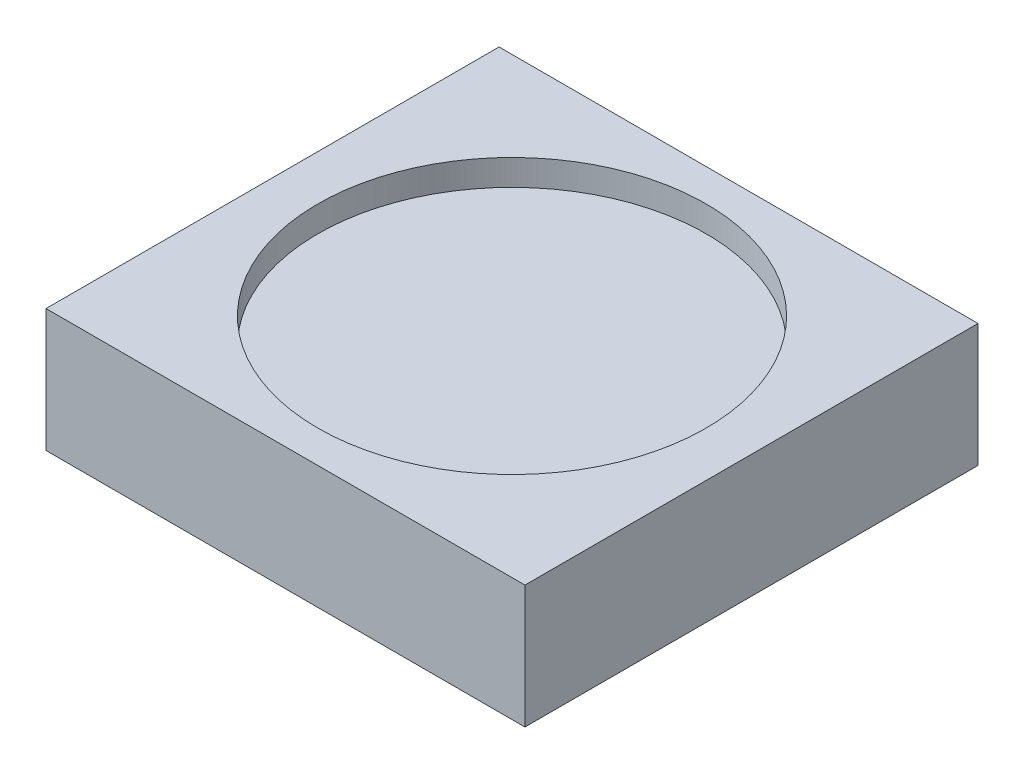
SolidWorks part; units mm, degrees
ref_plane "Front Plane" through (0, 0, 0) normal (0, 0, 1) x (1, 0, 0)
ref_plane "Top Plane" through (0, 0, 0) normal (0, 1, 0) x (1, 0, 0)
ref_plane "Right Plane" through (0, 0, 0) normal (1, 0, 0) x (0, 0, -1)
sketch "Sketch1" plane through (0, 0, 0) normal (0, 1, 0) x (1, 0, 0)
  line L1 (0, 0) -> (3.7, 0)
  line L2 (0, 0) -> (0, 3.5)
  line L3 (0, 3.5) -> (3.7, 3.5)
  line L4 (3.7, 0) -> (3.7, 3.5)
  dimension "D1" = 3.7
  dimension "D2" = 3.5
extrude "Boss-Extrude1" add sketch "Sketch1" along normal blind 0.95
sketch "Sketch2" plane through (0, 0.95, 0) normal (0, 1, 0) x (1, 0, 0)
  line L0 (0, 1.75) -> (3.7, 1.75) construction
  line L1 (0, 3.5) -> (0, 0) construction
  line L2 (3.7, 0) -> (3.7, 3.5) construction
  circle A0 centre (1.85, 1.75) radius 1.5
  point P8 (2.3744, 1.75)
  point P9 (2.5102, 1.75)
  point P10 (2.2425, 2.4418)
  point P11 (2.2909, 1.75)
  point P12 (1.85, 1.75)
  dimension "D1" = 3
extrude "Cut-Extrude1" cut sketch "Sketch2" against normal blind 0.2
